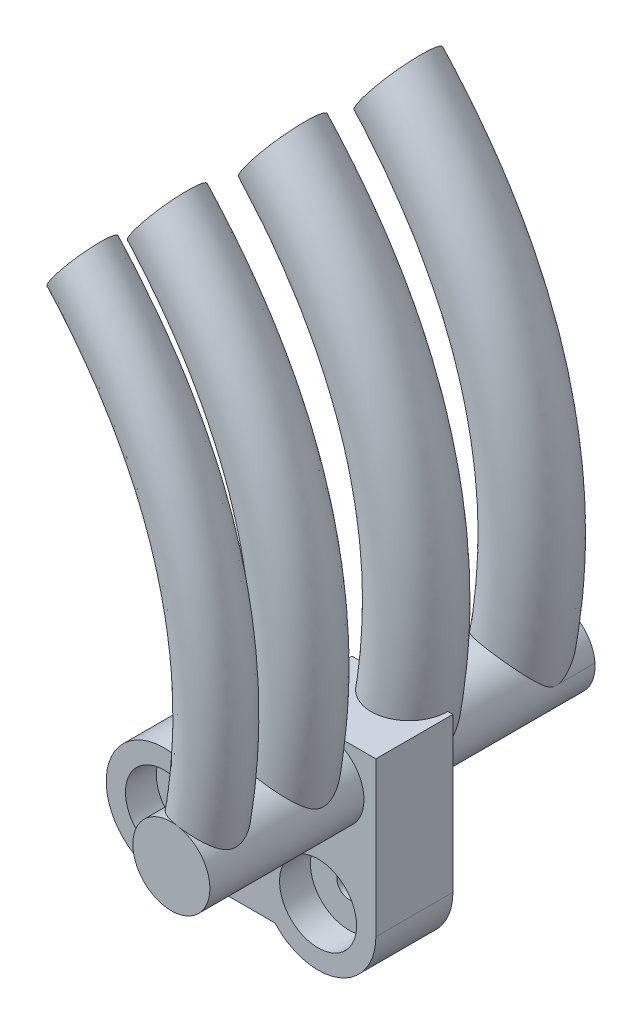
SolidWorks part; units mm, degrees
material "PLA"
ref_plane "Front Plane" through (0, 0, 0) normal (0, 0, 1) x (1, 0, 0)
ref_plane "Top Plane" through (0, 0, 0) normal (0, 1, 0) x (1, 0, 0)
ref_plane "Right Plane" through (0, 0, 0) normal (1, 0, 0) x (0, 0, -1)
sketch "Sketch1" plane through (0, 0, 0) normal (0, 0, 1) x (1, 0, 0)
  line L1 (4.4098, -5) -> (-4.4098, -5)
  line L3 (4.4098, 5) -> (-4.4098, 5)
  line L5 (2.6148, -1.3074) -> (0, 0) construction
  arc A0 (-2.6148, -1.3074) -> (-2.6148, 1.3074) centre (-10, 0) ccw
  arc A1 (4.4098, -5) -> (4.4098, 5) centre (10, 0) ccw
  circle A2 centre (-10, 0) radius 1.55
  circle A3 centre (10, 0) radius 1.55
  arc A4 (-4.4098, 5) -> (-4.4098, -5) centre (-10, 0) ccw
  point P0 (0, 0)
  dimension "D3" = 15
  dimension "D4" = 15
  dimension "D5" = 3.1
  dimension "D6" = 3.1
  dimension "D1" = 20
extrude "Boss-Extrude1" add sketch "Sketch1" along normal mid plane 10 contours A2 | L1 A4 L3 A1 | A3
sketch "Sketch2" plane through (0, 0, 5) normal (0, 0, 1) x (1, 0, 0)
  circle A0 centre (10, 0) radius 5
  dimension "D1" = 10
extrude "Cut-Extrude1" cut sketch "Sketch2" against normal blind 4
sketch "Sketch5" plane through (0, 0, -5) normal (0, 0, -1) x (-1, 0, 0)
  circle A0 centre (-10, 0) radius 5
  dimension "D1" = 10
extrude "Cut-Extrude3" cut sketch "Sketch5" against normal blind 4
sketch "Sketch6" plane through (0, 0, -5) normal (0, 0, -1) x (-1, 0, 0)
  line L0 (-17.5, 0) -> (-17.5, 20)
  line L1 (-4.4098, 5) -> (-4.4098, 20)
  line L2 (-4.4098, 20) -> (-17.5, 20)
  line L5 (4.4098, 5) -> (-4.4098, 5)
  line L6 (-4.4098, -5) -> (4.4098, -5)
  line L7 (4.4098, 5) -> (-4.4098, 5)
  line L8 (-4.4098, -5) -> (4.4098, -5)
  arc A0 (-4.4098, 5) -> (-4.4098, -5) centre (-10, 0) ccw construction
  circle A1 centre (-10, 0) radius 7.5
  arc A3 (-4.4098, 5) -> (-4.4098, -5) centre (-10, 0) ccw
  arc A4 (4.4098, -5) -> (4.4098, 5) centre (10, 0) ccw
  arc A5 (-17.5, 0) -> (-4.4098, -5) centre (-10, 0) ccw
  arc A6 (4.4098, -5) -> (4.4098, 5) centre (10, 0) ccw
  dimension "D1" = 20
  dimension "D2" = 0
extrude "Boss-Extrude2" add sketch "Sketch6" against normal blind 10
sketch "Sketch7" plane through (0, 0, 0) normal (0, 0, 1) x (1, 0, 0)
  line L0 (10.9549, 20) -> (10.9549, 10) construction
  line L1 (4.4098, 20) -> (17.5, 20) construction
  circle A0 centre (10.9549, 14.6458) radius 5
  dimension "D2" = 10
  dimension "D1" = 10
extrude "Boss-Extrude3" add sketch "Sketch7" along normal mid plane 50
ref_plane "Plane1" through (0, 15, 0) normal (0, 1, 0) x (1, 0, 0)
sketch "Sketch8" plane through (0, 15, 0) normal (0, 1, 0) x (1, 0, 0)
  line L0 (10.9549, 25) -> (10.9549, -25) construction
  line L1 (15.9549, 25) -> (5.9549, 25) construction
  line L2 (5.9549, -25) -> (15.9549, -25) construction
  circle A0 centre (10.9549, 20) radius 5
  circle A1 centre (10.9549, 5) radius 5
  circle A2 centre (10.9549, -10) radius 4.5
  circle A3 centre (10.9549, -21) radius 4
  dimension "D1" = 10
  dimension "D2" = 10
  dimension "D3" = 9
  dimension "D4" = 8
  dimension "D5" = 15
  dimension "D6" = 15
  dimension "D7" = 11
sketch "Sketch9" plane through (0, 0, 0) normal (0, 0, 1) x (1, 0, 0)
  line L0 (10.9549, 15) -> (10.9549, 75) construction
  line L1 (14.9549, 15) -> (6.9549, 15) construction
  line L2 (10.9549, 15) -> (-5.2439, 15) construction
  line L3 (19.371, 15) -> (-19.371, 15) construction
  line L4 (10.9549, 15) -> (-4.5742, 72.9555) construction
  spline S0 degree 2 poles (10.9549, 15) (18.2389, 47.8769) (-4.5742, 72.9555) knots 0 0 0 1 1 1
  point P8 (10.9549, 45)
  dimension "D1" = 15
  dimension "D2" = 60
sweep "Sweep1" add profiles "Sketch8" path "Sketch9"
sketch "Sketch10" plane through (0, 0, 5) normal (0, 0, 1) x (1, 0, 0)
  circle A0 centre (-10, 0) radius 5
  dimension "D1" = 10
extrude "Cut-Extrude4" cut sketch "Sketch10" against normal blind 4
